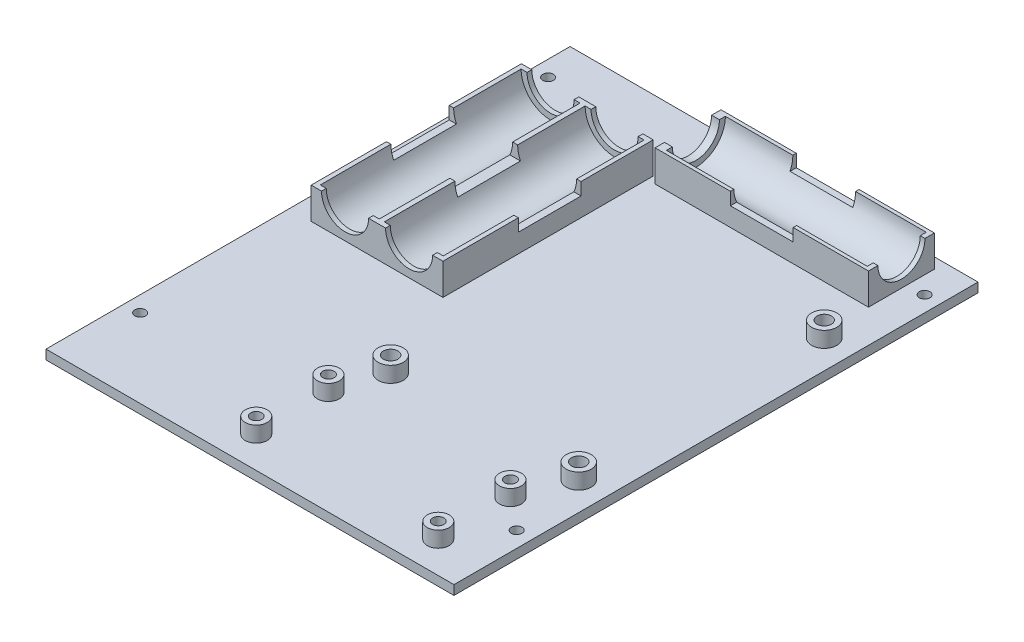
SolidWorks part; units mm, degrees
ref_plane "Plan de face" through (0, 0, 0) normal (0, 0, 1) x (1, 0, 0)
ref_plane "Plan de dessus" through (0, 0, 0) normal (0, 1, 0) x (1, 0, 0)
ref_plane "Plan de droite" through (0, 0, 0) normal (1, 0, 0) x (0, 0, -1)
sketch "Esquisse1" plane through (0, 0, 0) normal (0, 1, 0) x (1, 0, 0)
  line L1 (-65, -83.5) -> (65, -83.5)
  line L2 (-65, -83.5) -> (-65, 83.5)
  line L3 (-65, 83.5) -> (65, 83.5)
  line L4 (65, -83.5) -> (65, 83.5)
  line L5 (-65, -83.5) -> (65, 83.5) construction
  line L6 (-65, 83.5) -> (65, -83.5) construction
  point P0 (0, 0)
  dimension "D1" = 130
  dimension "D2" = 167
extrude "Boss.-Extru.1" add sketch "Esquisse1" along normal blind 3
sketch "Esquisse6" plane through (0, 3, 0) normal (0, 1, 0) x (1, 0, 0)
  line L2 (65, 83.5) -> (-65, 83.5) construction
  circle A0 centre (-8, -73.5) radius 3.5
  circle A1 centre (-8, -50.5) radius 3.5
  circle A2 centre (50, -50.5) radius 3.5
  circle A3 centre (50, -73.5) radius 3.5
  circle A4 centre (56, 43.5) radius 4
  circle A6 centre (56, -34.732) radius 4
  circle A7 centre (-3.436, -35.232) radius 4
  dimension "D1" = 7
  dimension "D9" = 8
  dimension "D7" = 59.436
  dimension "D2" = 58
  dimension "D3" = 23
  dimension "D4" = 10
  dimension "D5" = 15
  dimension "D6" = 0.5
  dimension "D8" = 78.232
  dimension "D10" = 9
  dimension "D11" = 40
extrude "Boss.-Extru.3" add sketch "Esquisse6" along normal blind 5
sketch "Esquisse11" plane through (-65, 0, 0) normal (-1, 0, 0) x (0, 0, 1)
  line L0 (-61, 3) -> (6, 3)
  line L1 (-61, 3) -> (-61, 13)
  line L2 (6, 3) -> (6, 13)
  line L3 (-61, 13) -> (6, 13)
  line L4 (-83.5, 3) -> (83.5, 3) construction
  dimension "D1" = 67
  dimension "D2" = 10
  dimension "D3" = 22.5
extrude "Boss.-Extru.6" add sketch "Esquisse11" against normal blind 49
sketch "Esquisse12" plane through (0, 0, 6) normal (0, 0, 1) x (1, 0, 0)
  line L0 (-65, 13) -> (-65, 3)
  line L1 (-65, 13) -> (-58, 13)
  line L2 (-65, 3) -> (-58, 3)
  line L3 (-58, 13) -> (-58, 3)
  line L4 (-16, 13) -> (-65, 13) construction
  circle A0 centre (-47.2, 13) radius 7.5
  circle A1 centre (-26.8, 13) radius 7.5
  dimension "D2" = 15
  dimension "D3" = 15
  dimension "D1" = 7
  dimension "D6" = 10.8
  dimension "D7" = 10.8
extrude "Enlèv. mat.-Extru.3" cut sketch "Esquisse12" against normal up to next
sketch "Esquisse13" plane through (0, 0, 6) normal (0, 0, 1) x (1, 0, 0)
  circle A0 centre (-47.2, 13) radius 9.4
  circle A1 centre (-26.8, 13) radius 9.4
  dimension "D3" = 18.8
  dimension "D4" = 18.8
  dimension "D1" = 10.8
  dimension "D2" = 10.8
extrude "Enlèv. mat.-Extru.4" cut sketch "Esquisse13" against normal blind 65.5
sketch "Esquisse14" plane through (0, 0, 6) normal (0, 0, 1) x (1, 0, 0)
  line L0 (-58, 13) -> (-54.7, 13)
  line L1 (-39.7, 13) -> (-34.3, 13)
  line L2 (-19.3, 13) -> (-16, 13)
  line L3 (-16, 13) -> (-16, 3)
  line L4 (-16, 3) -> (-58, 3)
  line L5 (-58, 3) -> (-58, 13)
  arc A0 (-54.7, 13) -> (-39.7, 13) centre (-47.2, 13) ccw
  arc A1 (-34.3, 13) -> (-19.3, 13) centre (-26.8, 13) ccw
extrude "Boss.-Extru.7" add sketch "Esquisse14" against normal blind 1.5
sketch "Esquisse15" plane through (-58, 0, 0) normal (-1, 0, 0) x (0, 0, 1)
  line L0 (-38, 13) -> (-38, 9)
  line L1 (-38, 13) -> (-18, 13)
  line L2 (-38, 9) -> (-18, 9)
  line L3 (-18, 13) -> (-18, 9)
  line L4 (-61, 13) -> (6, 13) construction
  dimension "D1" = 4
  dimension "D2" = 20
  dimension "D3" = 24
extrude "Enlèv. mat.-Extru.5" cut sketch "Esquisse15" against normal blind 43.7
sketch "Esquisse16" plane through (65, 0, 0) normal (1, 0, 0) x (0, 0, -1)
  line L0 (80.1, 3) -> (59.1, 3)
  line L1 (80.1, 3) -> (80.1, 13)
  line L2 (59.1, 3) -> (59.1, 13)
  line L3 (80.1, 13) -> (59.1, 13)
  line L4 (-83.5, 3) -> (83.5, 3) construction
  dimension "D1" = 10
  dimension "D2" = 21
  dimension "D3" = 3.4
extrude "Boss.-Extru.8" add sketch "Esquisse16" against normal blind 78.5
sketch "Esquisse17" plane through (0, 0, -80.1) normal (0, 0, -1) x (-1, 0, 0)
  line L0 (-65, 13) -> (-54.5, 13)
  line L1 (-65, 13) -> (-65, 3)
  line L2 (-54.5, 13) -> (-54.5, 3)
  line L3 (-65, 3) -> (-54.5, 3)
  line L4 (13.5, 13) -> (-65, 13) construction
  line L6 (-30.5, 13) -> (-30.5, 9)
  line L7 (-30.5, 13) -> (-10.5, 13)
  line L8 (-30.5, 9) -> (-10.5, 9)
  line L9 (-10.5, 13) -> (-10.5, 9)
  line L10 (-65, 3) -> (65, 3) construction
  dimension "D1" = 20
  dimension "D2" = 24
  dimension "D3" = 10.5
  dimension "D4" = 4
extrude "Enlèv. mat.-Extru.6" cut sketch "Esquisse17" against normal blind 24.2
sketch "Esquisse18" plane through (54.5, 0, 0) normal (1, 0, 0) x (0, 0, -1)
  line L0 (80.1, 13) -> (59.1, 13) construction
  circle A0 centre (69.6, 13) radius 7.5
  dimension "D1" = 15
extrude "Enlèv. mat.-Extru.7" cut sketch "Esquisse18" against normal up to next
sketch "Esquisse19" plane through (54.5, 0, 0) normal (1, 0, 0) x (0, 0, -1)
  circle A0 centre (69.6, 13) radius 9.4
  dimension "D1" = 18.8
extrude "Enlèv. mat.-Extru.8" cut sketch "Esquisse19" against normal blind 65.5
sketch "Esquisse20" plane through (54.5, 0, 0) normal (1, 0, 0) x (0, 0, -1)
  line L0 (59.1, 13) -> (62.1, 13)
  line L1 (77.1, 13) -> (80.1, 13)
  line L2 (80.1, 13) -> (80.1, 3)
  line L3 (80.1, 3) -> (59.1, 3)
  line L4 (59.1, 3) -> (59.1, 13)
  arc A0 (62.1, 13) -> (77.1, 13) centre (69.6, 13) ccw
extrude "Boss.-Extru.9" add sketch "Esquisse20" against normal blind 1.5
sketch "Esquisse21" plane through (0, 8, 0) normal (0, 1, 0) x (1, 0, 0)
  circle A0 centre (56, 43.5) radius 2.3
  circle A1 centre (56, -34.732) radius 2.3
  circle A2 centre (-3.436, -35.232) radius 2.3
  circle A3 centre (50, -50.5) radius 1.8
  circle A4 centre (50, -73.5) radius 1.8
  circle A5 centre (-8, -50.5) radius 1.8
  circle A6 centre (-8, -73.5) radius 1.8
  dimension "D1" = 4.6
  dimension "D2" = 3.6
extrude "Enlèv. mat.-Extru.9" cut sketch "Esquisse21" against normal blind 6.1
sketch "Esquisse22" plane through (0, 3, 0) normal (0, 1, 0) x (1, 0, 0)
  line L1 (65, -83.5) -> (65, 83.5) construction
  line L3 (65, 83.5) -> (-65, 83.5) construction
  circle A0 centre (-60, 71.5) radius 1.7
  circle A1 centre (60, 71.5) radius 1.7
  circle A2 centre (60, -58.5) radius 1.7
  circle A3 centre (-60, -58.5) radius 1.7
  dimension "D3" = 3.4
  dimension "D1" = 120
  dimension "D2" = 130
  dimension "D4" = 5
  dimension "D5" = 12
extrude "Enlèv. mat.-Extru.10" cut sketch "Esquisse22" against normal through all
